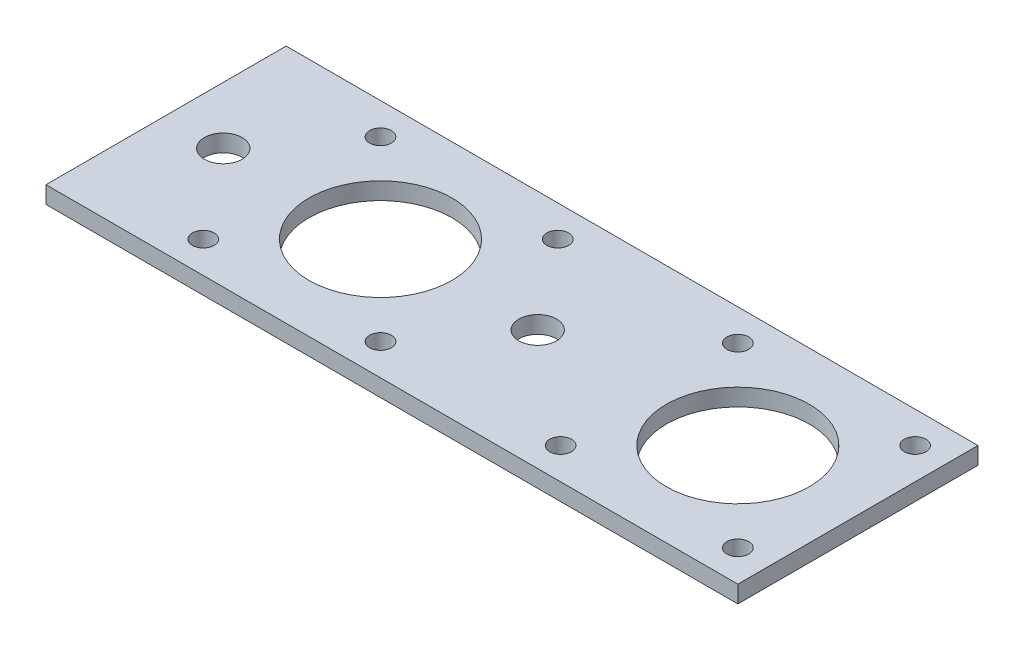
SolidWorks part; units mm, degrees
material "Thornel Mat VMA"
ref_plane "前视基准面" through (0, 0, 0) normal (0, 0, 1) x (1, 0, 0)
ref_plane "上视基准面" through (0, 0, 0) normal (0, 1, 0) x (1, 0, 0)
ref_plane "右视基准面" through (0, 0, 0) normal (1, 0, 0) x (0, 0, -1)
sketch "草图1" plane through (0, 0, 0) normal (0, 1, 0) x (1, 0, 0)
  line L1 (0, 0) -> (75, 0)
  line L2 (0, 0) -> (0, 42)
  line L3 (0, 42) -> (75, 42)
  line L4 (75, 0) -> (75, 42)
  dimension "D1" = 75
  dimension "D2" = 42
extrude "凸台-拉伸1" add sketch "草图1" along normal blind 3
sketch "草图2" plane through (0, 3, 0) normal (0, 1, 0) x (1, 0, 0)
  line L0 (0, 21) -> (75, 21)
  line L1 (0, 42) -> (0, 0) construction
  line L2 (75, 0) -> (75, 42) construction
  line L3 (75, 42) -> (0, 42) construction
  line L4 (0, 31) -> (20, 31)
  line L5 (0, 31) -> (0, 11)
  line L6 (0, 11) -> (20, 11)
  line L7 (20, 31) -> (20, 11)
  line L8 (0, 31) -> (20, 11) construction
  line L9 (0, 11) -> (20, 31) construction
  line L10 (55, 11) -> (75, 11)
  line L11 (55, 11) -> (55, 31)
  line L12 (55, 31) -> (75, 31)
  line L13 (75, 11) -> (75, 31)
  line L14 (55, 11) -> (75, 31) construction
  line L15 (55, 31) -> (75, 11) construction
  line L16 (16.5, 0) -> (58.5, 0)
  line L17 (16.5, 0) -> (16.5, 42)
  line L18 (16.5, 42) -> (58.5, 42)
  line L19 (58.5, 0) -> (58.5, 42)
  line L20 (16.5, 0) -> (58.5, 42) construction
  line L21 (16.5, 42) -> (58.5, 0) construction
  line L23 (22, 36.5) -> (53, 36.5)
  line L24 (22, 36.5) -> (22, 5.5)
  line L25 (22, 5.5) -> (53, 5.5)
  line L26 (53, 36.5) -> (53, 5.5)
  line L27 (22, 36.5) -> (53, 5.5) construction
  line L28 (22, 5.5) -> (53, 36.5) construction
  point P6 (10, 21)
  point P12 (65, 21)
  point P17 (37.5, 21)
  point P23 (37.5, 21)
  dimension "D1" = 20
  dimension "D2" = 20
  dimension "D3" = 20
  dimension "D4" = 20
  dimension "D5" = 42
  dimension "D6" = 31
  dimension "D7" = 31
sketch "草图3" plane through (0, 3, 0) normal (0, 1, 0) x (1, 0, 0)
  point P0 (22, 36.5)
  point P3 (53, 36.5)
  point P6 (53, 5.5)
  point P9 (22, 5.5)
hole_wizard "孔1" positions "草图3" profile "草图4" legacy end condition up to next
sketch "草图4" plane through (22, 3, -36.5) normal (1, 0, 0) x (0, 0, 1)
  line L0 (0, 0) -> (0, 3)
  line L1 (0, 3) -> (1.9, 3)
  line L2 (1.9, 3) -> (1.9, 0)
  line L3 (1.9, 0) -> (0, 0)
  line L4 (0, 110) -> (0, -10) construction
  dimension "直径" = 3.8
  dimension "深度" = 3
sketch "草图5" plane through (0, 3, 0) normal (0, 1, 0) x (1, 0, 0)
  line L0 (55, 31) -> (75, 11) construction
  point P0 (10, 21)
  point P3 (65, 21)
hole_wizard "孔2" positions "草图5" profile "草图6" legacy end condition up to next
sketch "草图6" plane through (10, 3, -21) normal (1, 0, 0) x (0, 0, 1)
  line L0 (0, 0) -> (0, 3)
  line L1 (0, 3) -> (3.3, 3)
  line L2 (3.3, 3) -> (3.3, 0)
  line L3 (3.3, 0) -> (0, 0)
  line L4 (0, 110) -> (0, -10) construction
  dimension "直径" = 6.6
  dimension "深度" = 3
hole_wizard "孔3" positions "草图7" profile "草图8" legacy end condition up to next
sketch "草图7" plane through (0, 3, 0) normal (0, 1, 0) x (1, 0, 0)
  point P0 (37.5, 21)
sketch "草图8" plane through (37.5, 3, -21) normal (1, 0, 0) x (0, 0, 1)
  line L0 (0, 0) -> (0, 3)
  line L1 (0, 3) -> (12.5, 3)
  line L2 (12.5, 3) -> (12.5, 0)
  line L3 (12.5, 0) -> (0, 0)
  line L4 (0, 110) -> (0, -10) construction
  dimension "直径" = 25
  dimension "深度" = 3
sketch "草图9" plane through (0, 3, 0) normal (0, 1, 0) x (1, 0, 0)
  line L0 (75, 21) -> (98, 21)
  line L2 (75, 42) -> (121, 42)
  line L3 (75, 42) -> (75, 0)
  line L4 (75, 0) -> (121, 0)
  line L5 (121, 42) -> (121, 0)
  line L6 (75, 42) -> (121, 0) construction
  line L7 (75, 0) -> (121, 42) construction
  dimension "D1" = 23
  dimension "D2" = 46
  dimension "D3" = 42
extrude "凸台-拉伸2" add sketch "草图9" against normal blind 3
sketch "草图10" plane through (0, 3, 0) normal (0, 1, 0) x (1, 0, 0)
  line L0 (0, 0) -> (121, 0) construction
  line L1 (121, 42) -> (79, 42)
  line L2 (121, 42) -> (121, 0)
  line L3 (121, 0) -> (79, 0)
  line L4 (79, 42) -> (79, 0)
  line L5 (79, 42) -> (121, 0)
  line L7 (84.5, 5.5) -> (115.5, 5.5)
  line L8 (84.5, 5.5) -> (84.5, 36.5)
  line L9 (84.5, 36.5) -> (115.5, 36.5)
  line L10 (115.5, 5.5) -> (115.5, 36.5)
  line L11 (84.5, 5.5) -> (115.5, 36.5) construction
  line L12 (84.5, 36.5) -> (115.5, 5.5) construction
  point P7 (100, 21)
  dimension "D1" = 42
  dimension "D2" = 31
  dimension "D3" = 31
sketch "草图11" plane through (0, 3, 0) normal (0, 1, 0) x (1, 0, 0)
  point P0 (84.5, 36.5)
  point P3 (115.5, 36.5)
  point P6 (115.5, 5.5)
  point P9 (84.5, 5.5)
hole_wizard "孔4" positions "草图11" profile "草图12" legacy end condition through all
sketch "草图12" plane through (84.5, 3, -36.5) normal (1, 0, 0) x (0, 0, 1)
  line L0 (0, 0) -> (0, 3)
  line L1 (0, 3) -> (1.9, 3)
  line L2 (1.9, 3) -> (1.9, 0)
  line L3 (1.9, 0) -> (0, 0)
  line L4 (0, 110) -> (0, -10) construction
  dimension "直径" = 3.8
  dimension "深度" = 3
sketch "草图13" plane through (0, 3, 0) normal (0, 1, 0) x (1, 0, 0)
  point P0 (100, 21)
hole_wizard "孔5" positions "草图13" profile "草图14" legacy end condition through all
sketch "草图14" plane through (100, 3, -21) normal (1, 0, 0) x (0, 0, 1)
  line L0 (0, 0) -> (0, 3)
  line L1 (0, 3) -> (12.5, 3)
  line L2 (12.5, 3) -> (12.5, 0)
  line L3 (12.5, 0) -> (0, 0)
  line L4 (0, 110) -> (0, -10) construction
  dimension "直径" = 25
  dimension "深度" = 3
